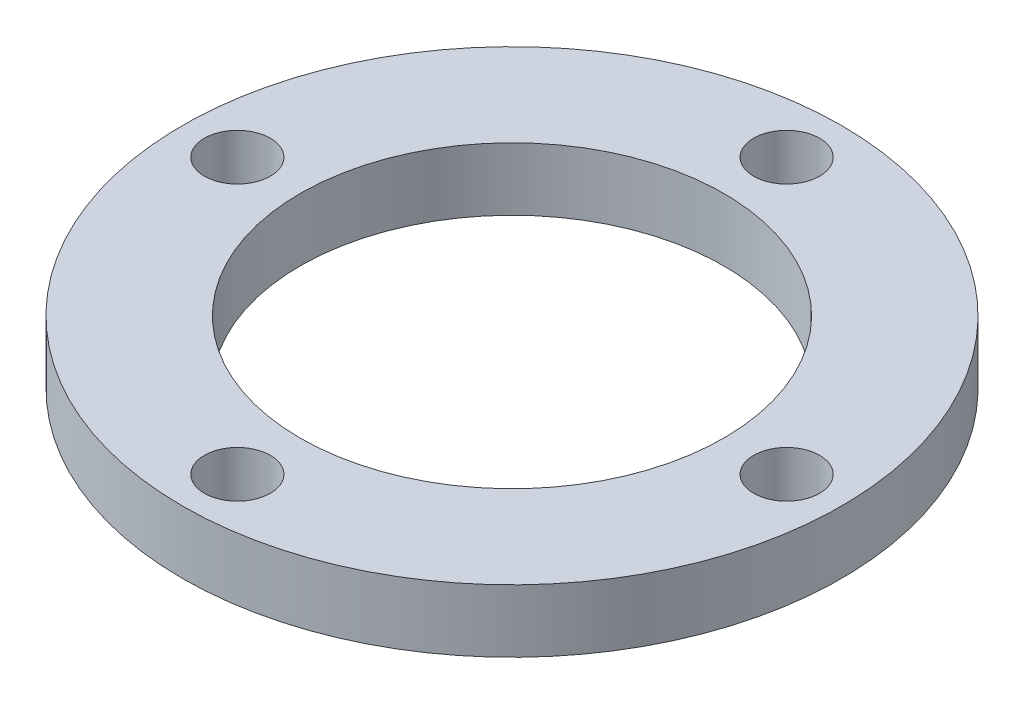
SolidWorks part; units mm, degrees
ref_plane "前视基准面" through (0, 0, 0) normal (0, 0, 1) x (1, 0, 0)
ref_plane "上视基准面" through (0, 0, 0) normal (0, 1, 0) x (1, 0, 0)
ref_plane "右视基准面" through (0, 0, 0) normal (1, 0, 0) x (0, 0, -1)
sketch "草图2" plane through (0, 0, 0) normal (0, 1, 0) x (1, 0, 0)
  circle A0 centre (0, 0) radius 21
  circle A1 centre (0, 0) radius 17.5 construction
  circle A2 centre (0, 0) radius 13.5
  circle A3 centre (0, 17.5) radius 2.1
  circle A4 centre (17.5, 0) radius 2.1
  circle A5 centre (0, -17.5) radius 2.1
  circle A6 centre (-17.5, 0) radius 2.1
  point P7 (-30.5461, 0)
  point P8 (0, 0)
  point P16 (0, 0)
  dimension "D2" = 42
  dimension "D3" = 35
  dimension "D4" = 4.2
  dimension "D5" = 27
  dimension "D1" = 4
extrude "凸台-拉伸1" add sketch "草图2" along normal blind 4
